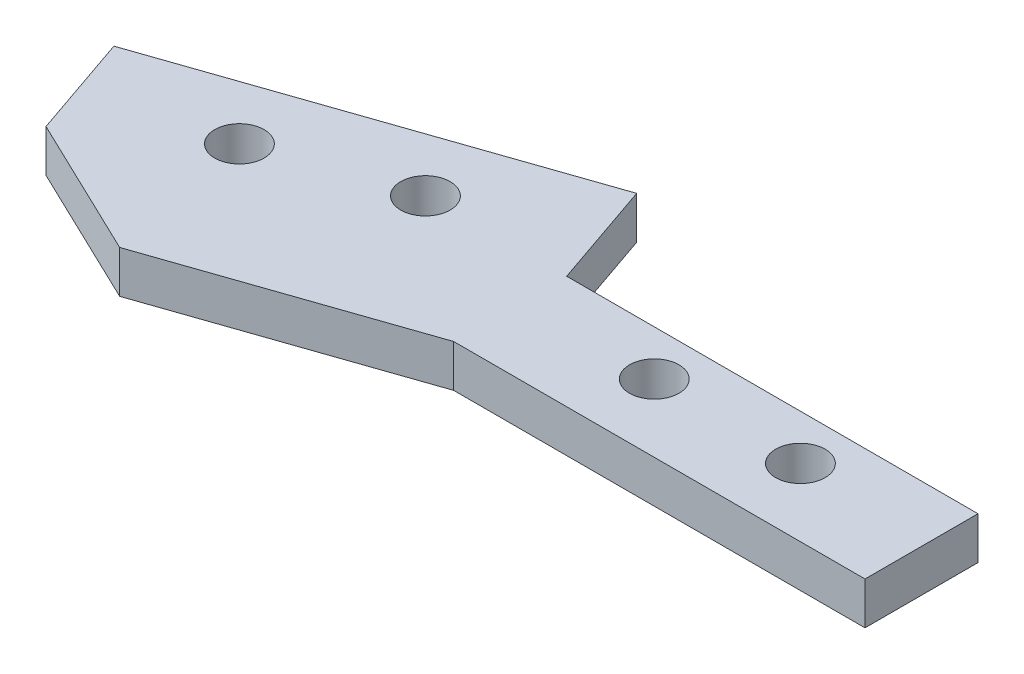
SolidWorks part; units mm, degrees
ref_plane "Front Plane" through (0, 0, 0) normal (0, 0, 1) x (1, 0, 0)
ref_plane "Top Plane" through (0, 0, 0) normal (0, 1, 0) x (1, 0, 0)
ref_plane "Right Plane" through (0, 0, 0) normal (1, 0, 0) x (0, 0, -1)
sketch "Sketch2" plane through (0, 0, 0) normal (0, 1, 0) x (1, 0, 0)
  line L0 (-50.2257, 28.6704) -> (-77.7687, 19.1866)
  line L1 (-50.2257, 28.6704) -> (-21.0956, 28.6704)
  line L2 (-50.2257, 28.6704) -> (-50.2257, 20.6672)
  line L3 (-50.2257, 20.6672) -> (-21.0956, 20.6672)
  line L4 (-21.0956, 28.6704) -> (-21.0956, 20.6672)
  line L5 (-50.2257, 20.6672) -> (-77.7687, 11.1834)
  line L6 (-77.7687, 19.1866) -> (-77.7687, 11.1834)
  dimension "D1" = 71
  dimension "D2" = 161
extrude "Boss-Extrude1" add sketch "Sketch2" along normal blind 3 contours L0 L6 L5 L2 | L4 L1 L2 L3
sketch "Sketch3" plane through (0, 0, 0) normal (0, -1, 0) x (1, 0, 0)
  line L0 (-30.4706, -25.4672) -> (-21.0956, -25.4704) construction
  line L2 (-21.0956, -28.6704) -> (-21.0956, -20.6672) construction
  line L3 (-30.4706, -25.4672) -> (-40.8206, -25.4672) construction
  line L4 (-21.0956, -25.4704) -> (-40.8206, -25.4672) construction
  line L5 (-40.8206, -25.4672) -> (-30.4706, -25.4672) construction
  circle A0 centre (-30.4706, -25.4672) radius 1.75
  circle A1 centre (-40.8206, -25.4672) radius 1.75
extrude "Cut-Extrude1" cut sketch "Sketch3" against normal blind 3
sketch "Sketch5" plane through (-14.1493, 0, -41.0926) normal (-0.3256, 0, -0.9455) x (-0.9455, 0, 0.3256)
  line L1 (38.1552, 3) -> (67.2852, 3)
  line L2 (38.1552, 3) -> (38.1552, 0)
  line L3 (38.1552, 0) -> (67.2852, 0)
  line L4 (67.2852, 3) -> (67.2852, 0)
extrude "Boss-Extrude2" add sketch "Sketch5" along normal blind 8
sketch "Sketch6" plane through (0, 0, 0) normal (0, -1, 0) x (1, 0, 0)
  line L0 (-50.2257, -28.6704) -> (-77.7687, -19.1866) construction
  line L1 (-77.7687, -19.1866) -> (-50.2257, -28.6704) construction
  line L2 (-50.2257, -28.6704) -> (-57.7507, -26.0794) construction
  line L4 (-69.9357, -25.2014) -> (-60.1598, -28.6007) construction
  circle A0 centre (-69.9357, -25.2014) radius 1.75
  circle A1 centre (-60.1598, -28.6007) radius 1.75
extrude "Cut-Extrude3" cut sketch "Sketch6" against normal blind 7
sketch "Sketch7" plane through (0, 0, 0) normal (0, -1, 0) x (1, 0, 0)
  line L0 (-77.7687, -19.1866) -> (-75.305, -12.0317)
  line L1 (-50.2257, -20.6672) -> (-77.7687, -11.1834) construction
  line L2 (-75.305, -12.0317) -> (-77.7687, -11.1834)
  line L3 (-77.7687, -11.1834) -> (-77.7687, -19.1866)
extrude "Cut-Extrude4" cut sketch "Sketch7" against normal blind 5
sketch "Sketch9" plane through (0, 0, 0) normal (0, -1, 0) x (1, 0, 0)
  line L0 (-80.3732, -26.7508) -> (-75.305, -12.0317) construction
  line L1 (-75.305, -12.0317) -> (-77.8391, -19.3912) construction
  line L2 (-77.8391, -19.3912) -> (-62.7654, -16.3494) construction
  line L3 (-50.2257, -20.6672) -> (-75.305, -12.0317) construction
  line L4 (-62.7654, -16.3494) -> (-75.305, -12.0317) construction
  line L5 (-75.305, -12.0317) -> (-69.0352, -14.1906) construction
  line L6 (-77.848, -19.4169) -> (-75.305, -12.0317)
  line L7 (-75.305, -12.0317) -> (-69.0352, -14.1906)
  spline S0 degree 2 poles (-69.0352, -14.1906) (-74.0867, -15.6862) (-77.848, -19.4169) knots 0 0 0 1 1 1
  line M5 (-50.2257, -20.6672) -> (-75.305, -12.0317)
  line M6 (-75.305, -12.0317) -> (-80.3732, -26.7508)
extrude "Cut-Extrude5" cut sketch "Sketch9" against normal blind 3 contours S0 M5 M6
sketch "Sketch10" plane through (0, 0, 0) normal (0, -1, 0) x (1, 0, 0)
  line L0 (-77.848, -19.4169) -> (-67.8223, -14.6082)
  line L1 (-50.2257, -20.6672) -> (-69.0352, -14.1906) construction
  line L2 (-67.8223, -14.6082) -> (-69.0352, -14.1906)
  line L3 (-67.8223, -14.6082) -> (-75.305, -12.0317)
  line L4 (-77.848, -19.4169) -> (-75.305, -12.0317)
  spline M8 degree 2 poles (-69.0352, -14.1906) (-74.0867, -15.6862) (-77.848, -19.4169) knots 0 0 0 1 1 1
  line M15 (-50.2257, -20.6672) -> (-69.0352, -14.1906)
extrude "Cut-Extrude7" cut sketch "Sketch10" against normal blind 10 contours L4 L3 M8 | L0 M8 M15
